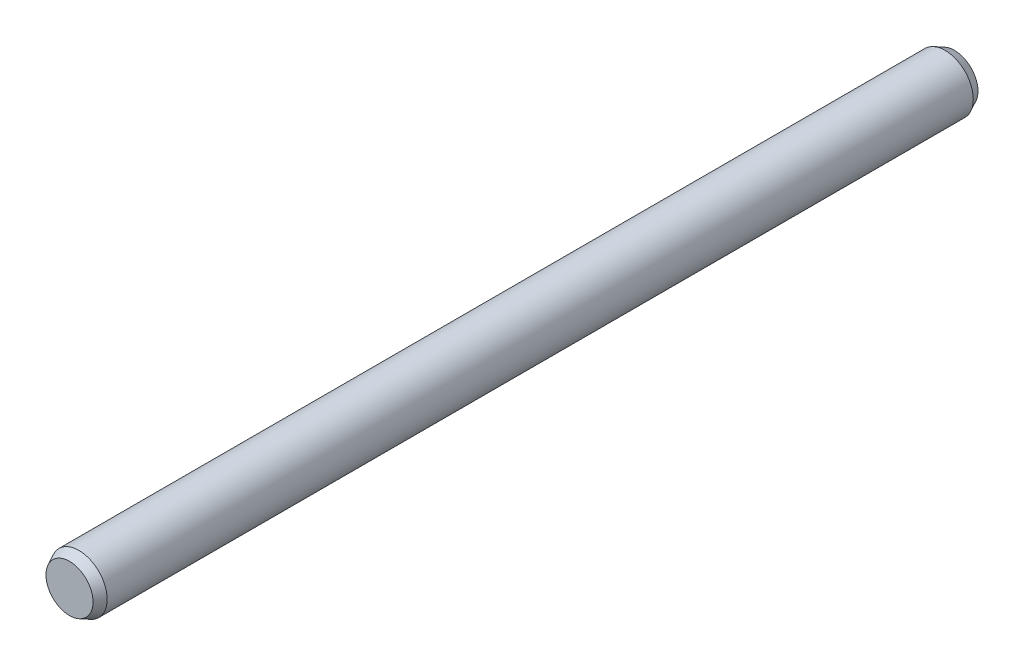
SolidWorks part; units mm, degrees
ref_plane "Plan de face" through (0, 0, 0) normal (0, 0, 1) x (1, 0, 0)
ref_plane "Plan de dessus" through (0, 0, 0) normal (0, 1, 0) x (1, 0, 0)
ref_plane "Plan de droite" through (0, 0, 0) normal (1, 0, 0) x (0, 0, -1)
sketch "Sketch2" plane through (0, 0, 0) normal (0, 0, 1) x (1, 0, 0)
  circle A0 centre (0, 0) radius 1.5
  dimension "D1" = 3
extrude "Boss-Extrude1" add sketch "Sketch2" along normal blind 47
cosmetic thread "Cosmetic Thread1" parameters "D2"=2.5
chamfer "Chamfer1" distance 0.5 distance2 0.25 1 edges at (1.5, 0, 47)
chamfer "Chamfer2" distance 0.25 distance2 0.5 1 edges at (1.5, 0, 0)
